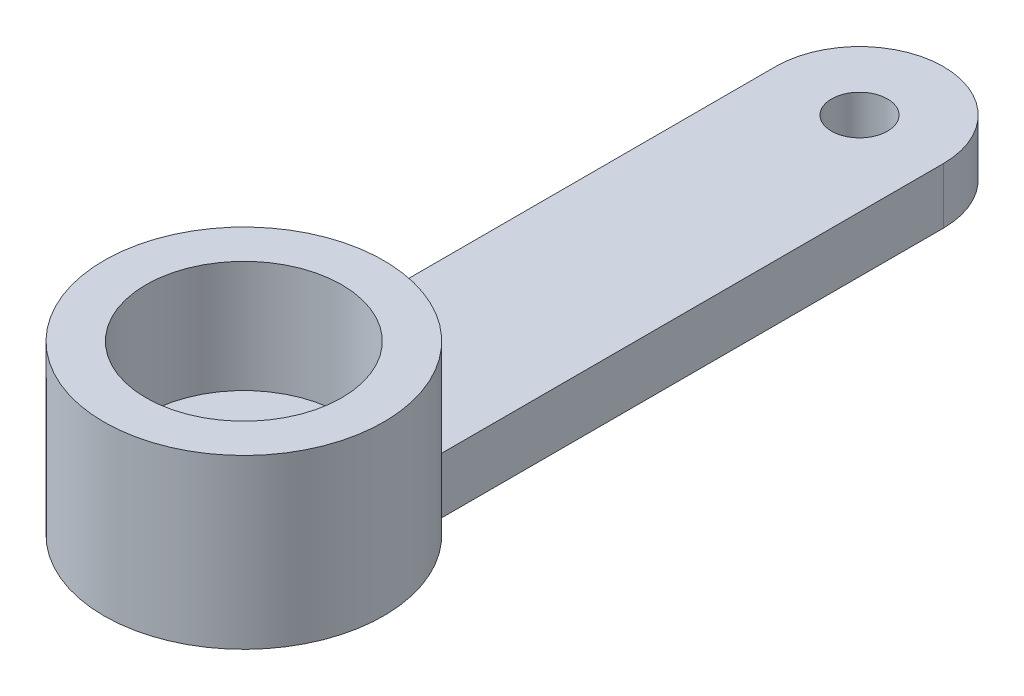
SolidWorks part; units mm, degrees
ref_plane "Front Plane" through (0, 0, 0) normal (0, 0, 1) x (1, 0, 0)
ref_plane "Top Plane" through (0, 0, 0) normal (0, 1, 0) x (1, 0, 0)
ref_plane "Right Plane" through (0, 0, 0) normal (1, 0, 0) x (0, 0, -1)
sketch "Sketch3" plane through (0, 0, 0) normal (0, 1, 0) x (1, 0, 0)
  line L0 (-1.5, 2) -> (-1.5, 11)
  line L1 (1.5, 11) -> (1.5, 2)
  circle A0 centre (0, 0) radius 2.5
  arc A1 (-1.5, 11) -> (1.5, 11) centre (0, 11) cw
  point P7 (0, 12.5)
  dimension "D1" = 5
  dimension "D4" = 12.5
  dimension "D2" = 3
  dimension "D3" = 1.5
extrude "Boss-Extrude2" add sketch "Sketch3" along normal blind 1 contours A1 L0 A0 L1 | A0
sketch "Sketch4" plane through (0, 1, 0) normal (0, 1, 0) x (1, 0, 0)
  circle A0 centre (0, 0) radius 2.5
  circle A1 centre (0, 0) radius 1.75
  dimension "D1" = 5
  dimension "D2" = 3.5
extrude "Boss-Extrude3" add sketch "Sketch4" along normal blind 2
sketch "Sketch5" plane through (0, 0, 0) normal (0, -1, 0) x (1, 0, 0)
  circle A0 centre (0, -11) radius 0.5
extrude "Cut-Extrude1" cut sketch "Sketch5" against normal blind 2
